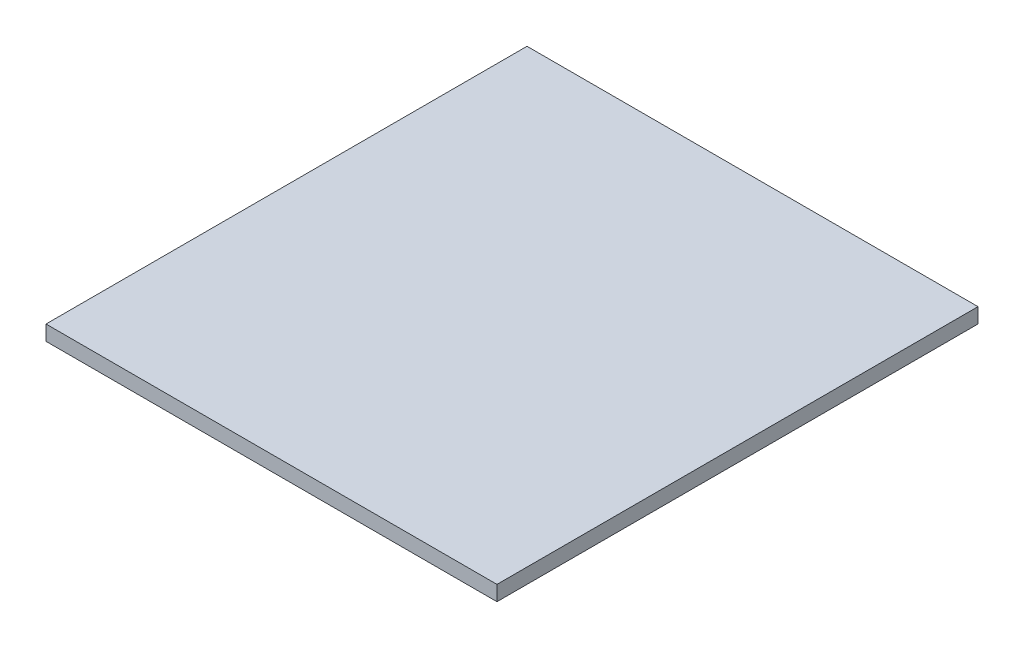
SolidWorks part; units mm, degrees
ref_plane "Front Plane" through (0, 0, 0) normal (0, 0, 1) x (1, 0, 0)
ref_plane "Top Plane" through (0, 0, 0) normal (0, 1, 0) x (1, 0, 0)
ref_plane "Right Plane" through (0, 0, 0) normal (1, 0, 0) x (0, 0, -1)
sketch "Sketch1" plane through (0, 0, 0) normal (0, 1, 0) x (1, 0, 0)
  line L1 (0, 0) -> (571.5, 0)
  line L2 (0, 0) -> (0, 609.6)
  line L3 (0, 609.6) -> (571.5, 609.6)
  line L4 (571.5, 0) -> (571.5, 609.6)
  dimension "D1" = 571.5
  dimension "D2" = 609.6
extrude "Boss-Extrude1" add sketch "Sketch1" along normal blind 19.05
